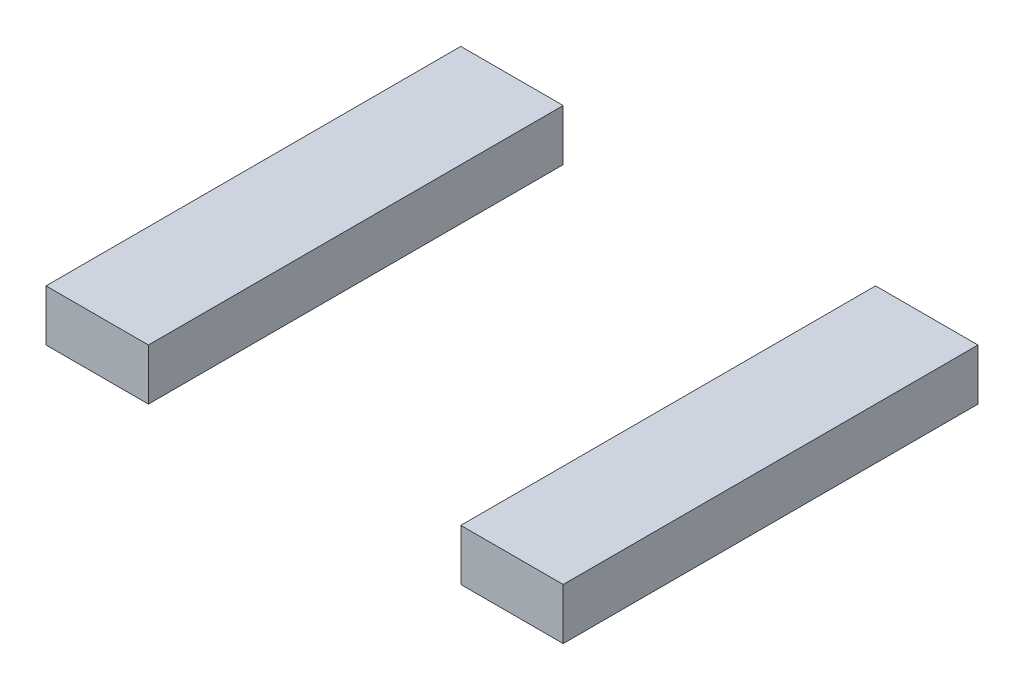
SolidWorks part; units mm, degrees
ref_plane "Front Plane" through (0, 0, 0) normal (0, 0, 1) x (1, 0, 0)
ref_plane "Top Plane" through (0, 0, 0) normal (0, 1, 0) x (1, 0, 0)
ref_plane "Right Plane" through (0, 0, 0) normal (1, 0, 0) x (0, 0, -1)
sketch "Sketch1" plane through (0, 0, 0) normal (0, 1, 0) x (1, 0, 0)
  line L0 (-30.5, 40.5) -> (30.5, 40.5) construction
  line L1 (-30.5, 40.5) -> (-50.5, 40.5)
  line L2 (-30.5, 40.5) -> (-30.5, -40.5)
  line L3 (-30.5, -40.5) -> (-50.5, -40.5)
  line L4 (-50.5, 40.5) -> (-50.5, -40.5)
  line L5 (30.5, 40.5) -> (50.5, 40.5)
  line L6 (30.5, 40.5) -> (30.5, -40.5)
  line L7 (30.5, -40.5) -> (50.5, -40.5)
  line L8 (50.5, 40.5) -> (50.5, -40.5)
  point P8 (0, 40.5)
  point P11 (-30.5, 0)
  point P14 (-40.5, 40.5)
  point P15 (40.5, 40.5)
  dimension "D1" = 20
  dimension "D3" = 40.5
  dimension "D4" = 81
extrude "Boss-Extrude1" add sketch "Sketch1" along normal blind 10
